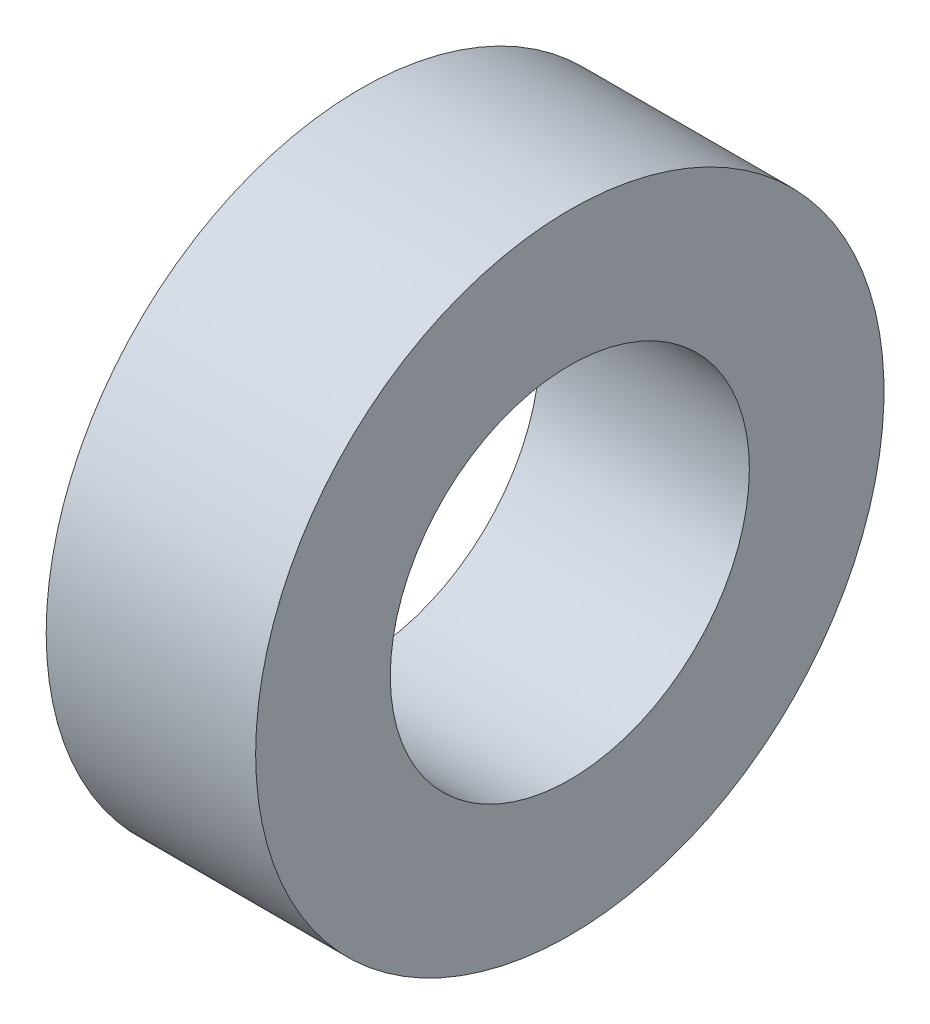
SolidWorks part; units mm, degrees
material "天然橡胶"
ref_plane "前视基准面" through (0, 0, 0) normal (0, 0, 1) x (1, 0, 0)
ref_plane "上视基准面" through (0, 0, 0) normal (0, 1, 0) x (1, 0, 0)
ref_plane "右视基准面" through (0, 0, 0) normal (1, 0, 0) x (0, 0, -1)
other "Configuration Table"
sketch "草图2" plane through (0, 0, 0) normal (0, 0, 1) x (1, 0, 0)
  line L0 (-18.6533, 0) -> (23.5239, 0) construction
  line L1 (0, 6) -> (7, 6)
  line L2 (7, 6) -> (7, 10.5)
  line L3 (7, 10.5) -> (0, 10.5)
  line L4 (0, 10.5) -> (0, 9.3)
  line L5 (0, 9.3) -> (5.5, 9.3)
  line L6 (5.5, 9.3) -> (5.5, 7.2)
  line L7 (5.5, 7.2) -> (0, 7.2)
  line L8 (0, 7.2) -> (0, 6)
  circle A0 centre (1.5, 7.2) radius 0.75
  point P13 (1.5128, 7.2)
  dimension "D1" = 1.5
  dimension "D2" = 1.5
  dimension "D3" = 6
  dimension "D4" = 1.2
  dimension "D5" = 1.2
  dimension "D6" = 7
  dimension "D7" = 1.5
  dimension "D8" = 10.5
revolve "旋转1" add sketch "草图2" angle 360 about L0
fillet "圆角1" radius 0.3 2 edges at (5.5, 0, 7.2) (5.5, 0, 9.3)
